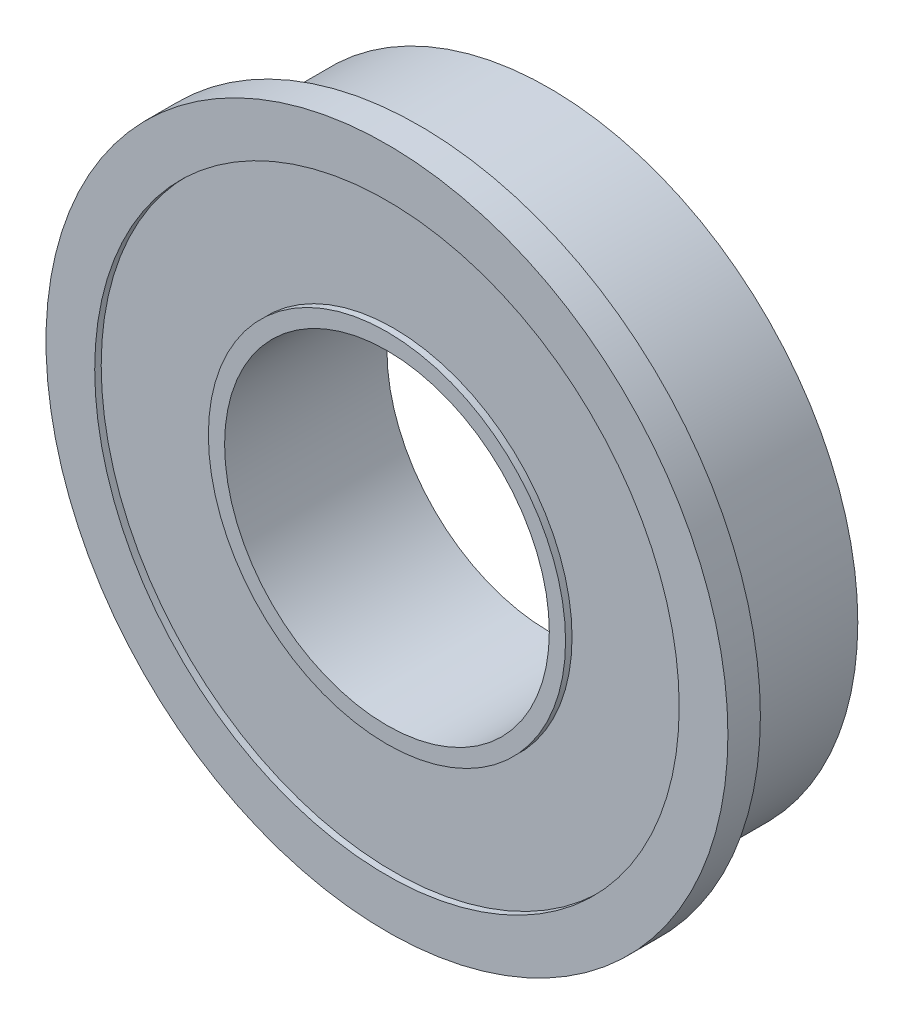
SolidWorks part; units mm, degrees
ref_plane "前视基准面" through (0, 0, 0) normal (0, 0, 1) x (1, 0, 0)
ref_plane "上视基准面" through (0, 0, 0) normal (0, 1, 0) x (1, 0, 0)
ref_plane "右视基准面" through (0, 0, 0) normal (1, 0, 0) x (0, 0, -1)
sketch "草图1" plane through (0, 0, 0) normal (0, 0, 1) x (1, 0, 0)
  circle A0 centre (0, 0) radius 9.5
  circle A1 centre (0, 0) radius 10.5
  dimension "D1" = 19
  dimension "D2" = 21
extrude "凸台-拉伸1" add sketch "草图1" along normal blind 1
sketch "草图2" plane through (0, 0, 1) normal (0, 0, 1) x (1, 0, 0)
  circle A0 centre (0, 0) radius 9.5
  circle A1 centre (0, 0) radius 5
  circle A3 centre (0, 0) radius 9.5 construction
  dimension "D2" = 10
extrude "凸台-拉伸2" add sketch "草图2" against normal blind 5
sketch "草图3" plane through (0, 0, -4) normal (0, 0, -1) x (-1, 0, 0)
  circle A0 centre (0, 0) radius 5.5
  circle A1 centre (0, 0) radius 9
  circle A2 centre (0, 0) radius 9.5 construction
  circle A3 centre (0, 0) radius 5 construction
  dimension "D1" = 0.5
  dimension "D2" = 0.5
extrude "切除-拉伸1" cut sketch "草图3" against normal blind 0.2
ref_plane "基准面1" through (0, 0, -1.5) normal (0, 0, -1) x (-1, 0, 0)
mirror "镜向1" about plane through (0, 0, -1.5) normal (0, 0, -1) of "切除-拉伸1"
